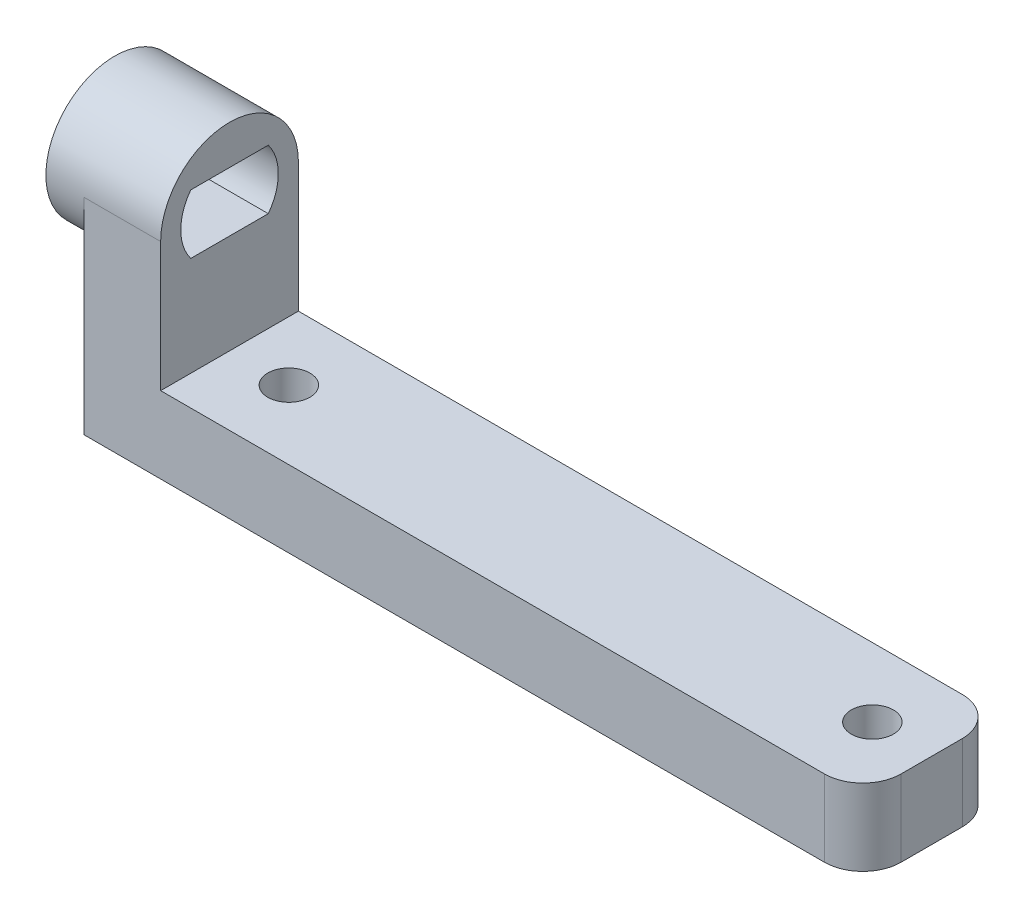
SolidWorks part; units mm, degrees
ref_plane "Front Plane" through (0, 0, 0) normal (0, 0, 1) x (1, 0, 0)
ref_plane "Top Plane" through (0, 0, 0) normal (0, 1, 0) x (1, 0, 0)
ref_plane "Right Plane" through (0, 0, 0) normal (1, 0, 0) x (0, 0, -1)
sketch "Sketch1" plane through (0, 0, 0) normal (0, 1, 0) x (1, 0, 0)
  line L0 (18.35, 0) -> (15.25, 0)
  line L1 (18.35, -3.6) -> (-18.35, -3.6)
  line L2 (18.35, -3.6) -> (18.35, 3.6)
  line L3 (18.35, 3.6) -> (-18.35, 3.6)
  line L4 (-18.35, -3.6) -> (-18.35, 3.6)
  line L5 (18.35, -3.6) -> (-18.35, 3.6) construction
  line L6 (18.35, 3.6) -> (-18.35, -3.6) construction
  line L7 (15.25, 0) -> (-15.25, 0)
  circle A0 centre (15.25, 0) radius 1.1
  circle A1 centre (-15.25, 0) radius 1.1
  point P0 (0, 0)
  dimension "D4" = 2.2
  dimension "D6" = 2.2
  dimension "D1" = 36.7
  dimension "D2" = 7.2
  dimension "D3" = 3.1
  dimension "D5" = 30.5
extrude "Boss-Extrude1" add sketch "Sketch1" along normal blind 4
sketch "Sketch2" plane through (0, 0, 0) normal (0, -1, 0) x (1, 0, 0)
  line L1 (-18.35, 3.6) -> (-22.35, 3.6)
  line L2 (-18.35, 3.6) -> (-18.35, -3.6)
  line L3 (-18.35, -3.6) -> (-22.35, -3.6)
  line L4 (-22.35, 3.6) -> (-22.35, -3.6)
  dimension "D1" = 4
extrude "Boss-Extrude2" add sketch "Sketch2" against normal blind 10.75
sketch "Sketch3" plane through (-18.35, 0, 0) normal (1, 0, 0) x (0, 0, -1)
  line L0 (3.6, 10.75) -> (-3.6, 10.75) construction
  circle A0 centre (0, 10.75) radius 3.6
extrude "Boss-Extrude3" add sketch "Sketch3" against normal blind 6
fillet "Fillet1" radius 2 2 edges at (18.35, 2, -3.6) (18.35, 2, 3.6)
sketch "Sketch4" plane through (-24.35, 0, 0) normal (-1, 0, 0) x (0, 0, 1)
  line L0 (0, 9.2) -> (0, 12.3)
  line L1 (2.0248, 12.3) -> (-2.0248, 12.3)
  line L2 (2.0248, 9.2) -> (-2.0248, 9.2)
  circle A0 centre (0, 10.75) radius 2.55
  point P7 (0, 10.75)
  point P10 (0, 12.3)
  point P13 (0, 9.2)
  dimension "D1" = 5.1
  dimension "D2" = 3.1
extrude "Cut-Extrude1" cut sketch "Sketch4" against normal up to surface (6 mm away) contours L1 A0 L2 L0 | L2 A0 L1 L0 up to face at (-18.35, 8.275, 0)
